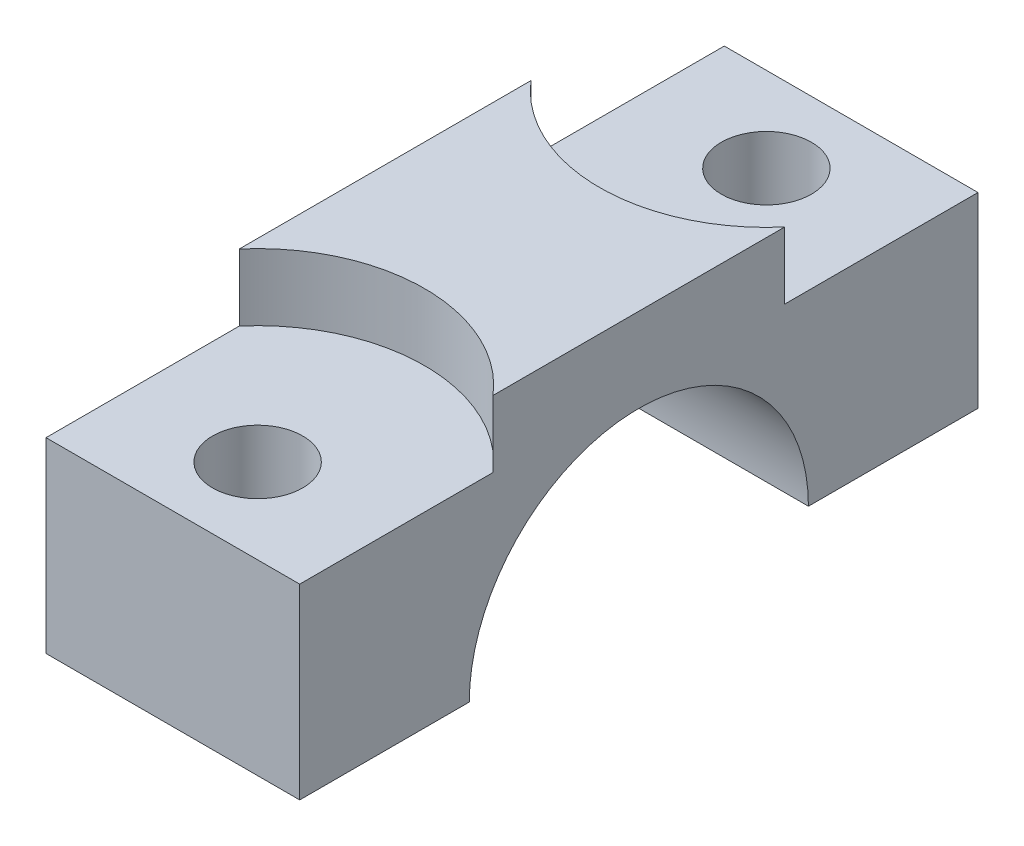
SolidWorks part; units mm, degrees
ref_plane "Front Plane" through (0, 0, 0) normal (0, 0, 1) x (1, 0, 0)
ref_plane "Top Plane" through (0, 0, 0) normal (0, 1, 0) x (1, 0, 0)
ref_plane "Right Plane" through (0, 0, 0) normal (1, 0, 0) x (0, 0, -1)
sketch "Sketch1" plane through (0, 0, 0) normal (1, 0, 0) x (0, 0, -1)
  line L0 (12.7, 0) -> (25.4, 0)
  line L1 (-25.4, 19) -> (25.4, 19)
  line L2 (-25.4, 19) -> (-25.4, 0)
  line L3 (-25.4, 0) -> (-12.7, 0)
  line L4 (25.4, 19) -> (25.4, 0)
  line L5 (-25.4, 19) -> (25.4, 0) construction
  line L6 (-25.4, 0) -> (25.4, 19) construction
  arc A0 (-12.7, 0) -> (12.7, 0) centre (0, 0) cw
  point P0 (0, 9.5)
  point P9 (0, 19)
  dimension "D3" = 12.7
  dimension "D1" = 50.8
  dimension "D2" = 19
extrude "Boss-Extrude1" add sketch "Sketch1" along normal mid plane 19
sketch "Sketch2" plane through (0, 0, 0) normal (0, -1, 0) x (1, 0, 0)
  line L0 (-9.5, 19.05) -> (9.5, 19.05) construction
  line L1 (-9.5, 25.4) -> (-9.5, 12.7) construction
  line L2 (9.5, 25.4) -> (9.5, 12.7) construction
  line L3 (-9.5, -19.05) -> (9.5, -19.05) construction
  line L4 (-9.5, -12.7) -> (-9.5, -25.4) construction
  line L5 (9.5, -12.7) -> (9.5, -25.4) construction
  point P12 (0, 19.05)
  point P13 (0, -19.05)
hole_wizard "CBORE for M12 Hex Head Cap Screw1" positions "Sketch3" profile "Sketch4" counterbore size "M12" standard "ISO" end condition through all
sketch "Sketch3" plane through (0, 19, 0) normal (0, 1, 0) x (1, 0, 0)
  point P0 (0, 19.05)
  point P3 (0, -19.05)
sketch "Sketch4" plane through (0, 19, -19.05) normal (1, 0, 0) x (0, 0, 1)
  line L0 (0, 0) -> (0, 19)
  line L1 (0, 19) -> (3.375, 19)
  line L3 (3.375, 19) -> (3.375, 5)
  line L4 (3.375, 5) -> (12.5, 5)
  line L5 (12.5, 5) -> (12.5, 0)
  line L7 (12.5, 0) -> (0, 0)
  line L11 (0, -6.35) -> (0, 107.95) construction
  dimension "Thru Hole Dia." = 6.75
  dimension "Thru Hole Depth" = 19
  dimension "C'Bore Dia." = 25
  dimension "C'Bore Depth" = 5
